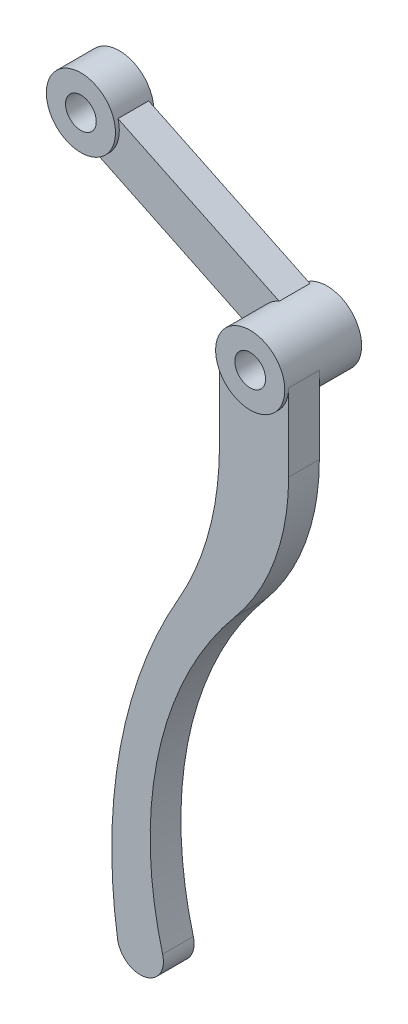
SolidWorks part; units mm, degrees
ref_plane "前视基准面" through (0, 0, 0) normal (0, 0, 1) x (1, 0, 0)
ref_plane "上视基准面" through (0, 0, 0) normal (0, 1, 0) x (1, 0, 0)
ref_plane "右视基准面" through (0, 0, 0) normal (1, 0, 0) x (0, 0, -1)
sketch "草图1" plane through (0, 0, 0) normal (0, 0, 1) x (1, 0, 0)
  circle A0 centre (0, 0) radius 9
  circle A1 centre (0, 0) radius 4
  circle A2 centre (-54.0756, 25.9966) radius 9
  circle A3 centre (-54.0756, 25.9966) radius 4
  dimension "D1" = 18
  dimension "D2" = 8
  dimension "D3" = 60
extrude "凸台-拉伸1" add sketch "草图1" along normal blind 10
sketch "草图2" plane through (0, 0, 10) normal (0, 0, 1) x (1, 0, 0)
  line L0 (-54.0756, 25.9966) -> (-8.1113, 3.8995) construction
  line L1 (-50.6295, 17.6825) -> (-8.6455, -2.5011)
  line L2 (-45.4301, 28.4977) -> (-3.4462, 8.3141)
  line L3 (-51.476, 31.4042) -> (2.5997, 5.4076) construction
  line L4 (-56.6753, 20.5891) -> (-2.5997, -5.4076) construction
  line L5 (-54.0756, 25.9966) -> (0, 0) construction
  circle A0 centre (0, 0) radius 9 construction
  circle A1 centre (-54.0756, 25.9966) radius 9 construction
  arc A2 (-3.4462, 8.3141) -> (-8.6455, -2.5011) centre (0, 0) ccw
  arc A3 (-50.6295, 17.6825) -> (-45.4301, 28.4977) centre (-54.0756, 25.9966) ccw
  dimension "D1" = 6
  dimension "D2" = 6
extrude "凸台-拉伸2" add sketch "草图2" against normal blind 8 from offset 1 offset against normal yes
sketch "草图4" plane through (0, 0, 10) normal (0, 0, 1) x (1, 0, 0)
  line L0 (-9, 0) -> (-9, -22)
  line L1 (9, 0) -> (9, -20.1308)
  line L2 (67.957, -119.5) -> (67.957, -3.9854) construction
  line L3 (-29.6015, -145.6407) -> (67.957, -119.5) construction
  circle A0 centre (0, 0) radius 9 construction
  arc A1 (-3.4462, 8.3141) -> (-8.6455, -2.5011) centre (0, 0) ccw construction
  arc A2 (-9, -22) -> (-19.6806, -61.9352) centre (-89, -22) cw
  arc A3 (-19.6806, -61.9352) -> (-35.5321, -146.5509) centre (92.9634, -126.83) ccw
  arc A4 (-35.5321, -146.5509) -> (-23.806, -144.0878) centre (-29.6015, -145.6407) ccw
  arc A5 (-23.806, -144.0878) -> (-4.9521, -58.5963) centre (67.957, -119.5) cw
  arc A6 (-4.9521, -58.5963) -> (9, -20.1308) centre (-51, -20.1308) ccw
  arc A7 (-9, 0) -> (9, 0) centre (0, 0) ccw
  point P19 (-24.8138, -99.0408)
  point P20 (-34.8138, -102.8929)
  dimension "D2" = 80
  dimension "D3" = 130
  dimension "D4" = 6
  dimension "D5" = 95
  dimension "D6" = 60
  dimension "D9" = 10
  dimension "D1" = 22
  dimension "D7" = 119.5
  dimension "D8" = 105
extrude "凸台-拉伸3" add sketch "草图4" along normal blind 8 from offset 1 separate body
sketch "草图5" plane through (0, 0, 10) normal (0, 0, 1) x (1, 0, 0)
  circle A0 centre (0, 0) radius 9 construction
  circle A1 centre (0, 0) radius 4 construction
  circle A2 centre (0, 0) radius 9
  circle A3 centre (0, 0) radius 4
extrude "凸台-拉伸4" add sketch "草图5" along normal blind 10
